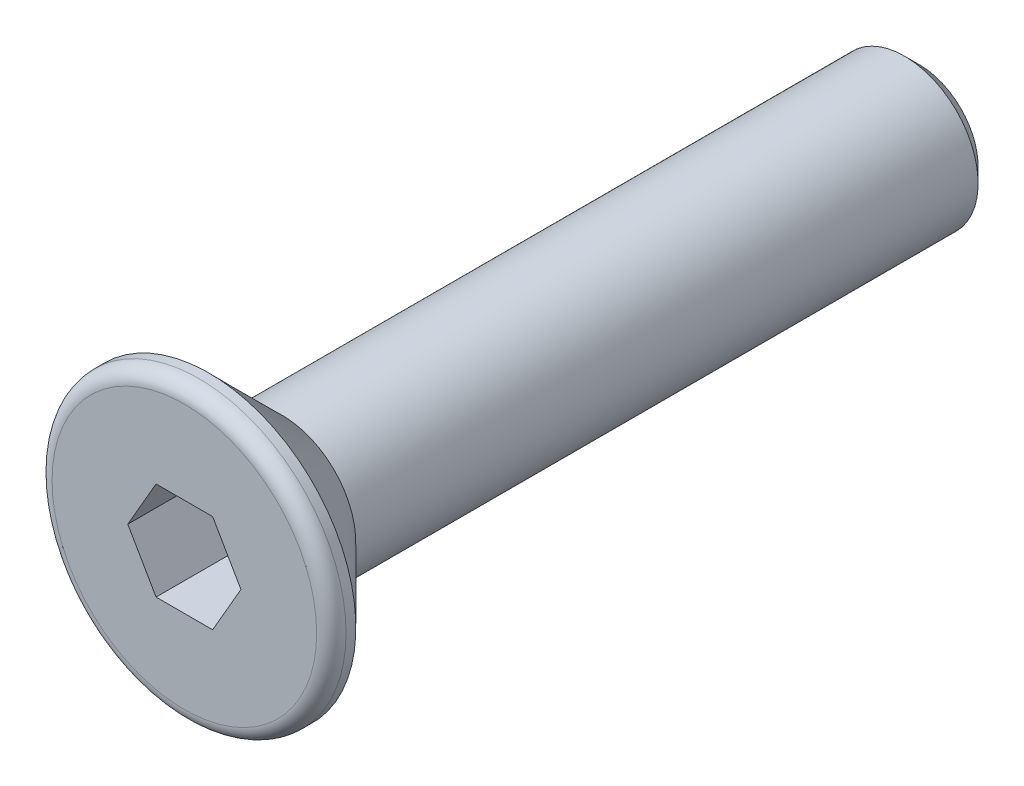
SolidWorks part; units mm, degrees
ref_plane "前视基准面" through (0, 0, 0) normal (0, 0, 1) x (1, 0, 0)
ref_plane "上视基准面" through (0, 0, 0) normal (0, 1, 0) x (1, 0, 0)
ref_plane "右视基准面" through (0, 0, 0) normal (1, 0, 0) x (0, 0, -1)
sketch "草图1" plane through (0, 0, 0) normal (1, 0, 0) x (0, 0, -1)
  line L0 (-7.5, 0) -> (-7.5, 3)
  line L1 (-7.5, 3) -> (-7, 3)
  line L2 (-7, 3) -> (-5.5, 1.5)
  line L3 (-5.5, 1.5) -> (7.2, 1.5)
  line L4 (7.2, 1.5) -> (7.5, 1.2)
  line L5 (7.5, 1.2) -> (7.5, 0)
  line L6 (7.5, 0) -> (-7.5, 0)
  dimension "D1" = 15
  dimension "D2" = 3
  dimension "D3" = 45
  dimension "D4" = 0.3
  dimension "D5" = 2
  dimension "D6" = 1.5
revolve "旋转1" add sketch "草图1" angle 360 about L6
sketch "草图2" plane through (0, 0, 7.5) normal (0, 0, 1) x (1, 0, 0)
  line L1 (1.1547, 0) -> (0.5774, 1)
  line L2 (0.5774, 1) -> (-0.5774, 1)
  line L3 (-0.5774, 1) -> (-1.1547, 0)
  line L4 (-1.1547, 0) -> (-0.5774, -1)
  line L5 (-0.5774, -1) -> (0.5774, -1)
  line L6 (0.5774, -1) -> (1.1547, 0)
  circle A0 centre (0, 0) radius 1 construction
  dimension "D1" = 2
extrude "切除-拉伸1" cut sketch "草图2" against normal blind 1.5
fillet "圆角1" radius 0.3 1 edges at (-3, 0, 7.5)
